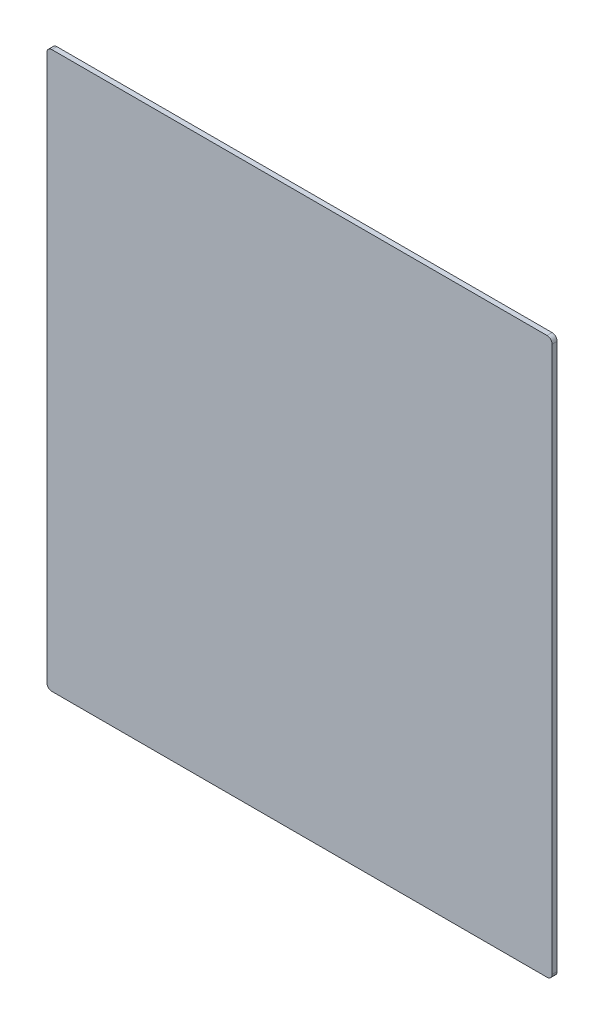
SolidWorks part; units mm, degrees
ref_plane "前视基准面" through (0, 0, 0) normal (0, 0, 1) x (1, 0, 0)
ref_plane "上视基准面" through (0, 0, 0) normal (0, 1, 0) x (1, 0, 0)
ref_plane "右视基准面" through (0, 0, 0) normal (1, 0, 0) x (0, 0, -1)
sketch "草图1" plane through (0, 0, 0) normal (0, 0, 1) x (1, 0, 0)
  line L1 (0, 0) -> (300, 0)
  line L2 (0, 0) -> (0, 330)
  line L3 (0, 330) -> (300, 330)
  line L4 (300, 0) -> (300, 330)
extrude "凸台-拉伸1" add sketch "草图1" along normal blind 3
fillet "圆角1" radius 3 4 edges at (0, 0, 1.5) (300, 0, 1.5) (300, 330, 1.5) (0, 330, 1.5)
